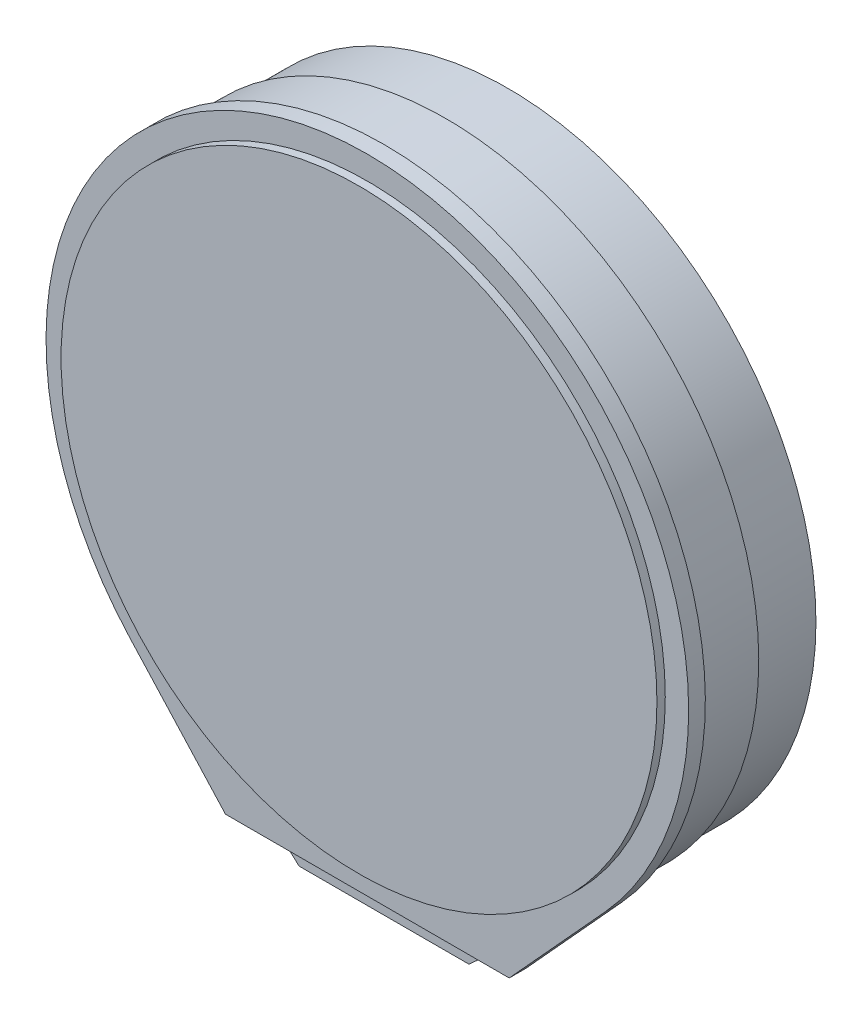
SolidWorks part; units mm, degrees
ref_plane "正面" through (0, 0, 0) normal (0, 0, 1) x (1, 0, 0)
ref_plane "平面" through (0, 0, 0) normal (0, 1, 0) x (1, 0, 0)
ref_plane "右側面" through (0, 0, 0) normal (1, 0, 0) x (0, 0, -1)
sketch "ｽｹｯﾁ1" plane through (0, 0, 0) normal (0, 0, 1) x (1, 0, 0)
  line L0 (-12.64, -13.8489) -> (-5.0898, -20.74)
  line L1 (-5.0898, -20.74) -> (5.0898, -20.74)
  line L2 (5.0898, -20.74) -> (12.64, -13.8489)
  line L3 (0, 26.0938) -> (0, -25.679) construction
  arc A0 (-12.64, -13.8489) -> (12.64, -13.8489) centre (0, 0) cw
  dimension "D1" = 18.75
  dimension "D3" = 25.28
  dimension "D2" = 39.49
  dimension "D4" = 6.8911
extrude "ﾎﾞｽ - 押し出し1" add sketch "ｽｹｯﾁ1" against normal blind 3.7
sketch "ｽｹｯﾁ2" plane through (0, 0, 0) normal (0, 0, 1) x (1, 0, 0)
  line L0 (-14.2263, -12.9683) -> (-8.5, -19.25)
  line L1 (-8.5, -19.25) -> (8.5, -19.25)
  line L2 (8.5, -19.25) -> (14.2263, -12.9683)
  line L3 (0, 23.9586) -> (0, -27.9597) construction
  arc A0 (14.2263, -12.9683) -> (-14.2263, -12.9683) centre (0, 0) ccw
  dimension "D1" = 38.5
  dimension "D2" = 17
extrude "ﾎﾞｽ - 押し出し2" add sketch "ｽｹｯﾁ2" along normal blind 1
sketch "ｽｹｯﾁ3" plane through (0, 0, 1) normal (0, 0, 1) x (1, 0, 0)
  circle A0 centre (0, 0) radius 17.85
  dimension "D1" = 35.7
extrude "ﾎﾞｽ - 押し出し3" add sketch "ｽｹｯﾁ3" along normal blind 0.5
sketch "ｽｹｯﾁ4" plane through (0, 0, 0) normal (0, 0, 1) x (1, 0, 0)
  circle A0 centre (0, 0) radius 18.4766
extrude "ﾎﾞｽ - 押し出し4" add sketch "ｽｹｯﾁ4" against normal blind 7.4
sketch "ｽｹｯﾁ5" plane through (0, -20.74, 0) normal (0, -1, 0) x (1, 0, 0)
  line L0 (-2.9, -5.3) -> (2.9, -5.3) construction
  line L1 (-2.9, -3.7) -> (2.9, -3.7)
  line L2 (-2.9, -6.9) -> (2.9, -6.9)
  line L3 (-5.0898, -3.7) -> (5.0898, -3.7) construction
  arc A0 (-2.9, -3.7) -> (-2.9, -6.9) centre (-2.9, -5.3) ccw
  arc A1 (2.9, -6.9) -> (2.9, -3.7) centre (2.9, -5.3) ccw
  point P2 (0, -5.3)
  point P7 (0.5374, -5.6694)
  point P10 (0, 0)
  dimension "D2" = 9
  dimension "D1" = 3.2
extrude "ﾎﾞｽ - 押し出し5" add sketch "ｽｹｯﾁ5" along normal blind 0.85 and the other way up to next
equation "\"D1@ﾎﾞｽ - 押し出し1\"=3.70"
